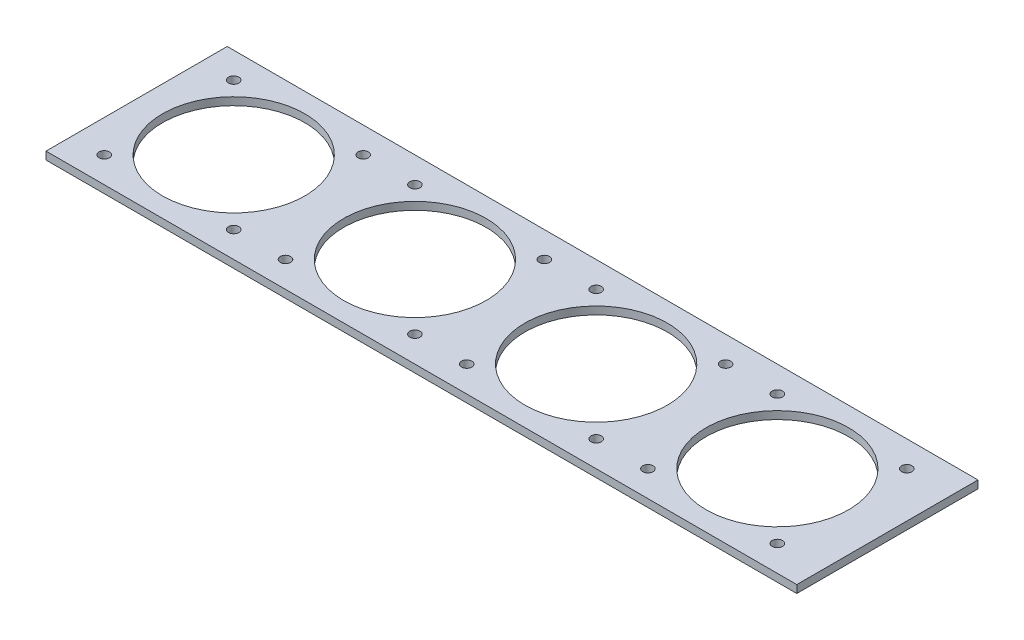
SolidWorks part; units mm, degrees
ref_plane "Ön Düzlem" through (0, 0, 0) normal (0, 0, 1) x (1, 0, 0)
ref_plane "Üst Düzlem" through (0, 0, 0) normal (0, 1, 0) x (1, 0, 0)
ref_plane "Sağ Düzlem" through (0, 0, 0) normal (1, 0, 0) x (0, 0, -1)
sketch "Çizim1" plane through (0, 0, 0) normal (0, 1, 0) x (1, 0, 0)
  line L0 (0, 35) -> (290, 35) construction
  line L1 (0, 0) -> (290, 0)
  line L2 (0, 0) -> (0, 70)
  line L3 (0, 70) -> (290, 70)
  line L4 (290, 0) -> (290, 70)
  line L5 (37.5, 35) -> (37.5, 7.5) construction
  circle A0 centre (37.5, 35) radius 27.5
  circle A1 centre (12.5, 60) radius 2
  circle A2 centre (62.5, 60) radius 2
  circle A3 centre (62.5, 10) radius 2
  circle A4 centre (12.5, 10) radius 2
  circle A5 centre (107.5, 35) radius 27.5
  circle A6 centre (132.5, 60) radius 2
  circle A7 centre (132.5, 10) radius 2
  circle A8 centre (82.5, 10) radius 2
  circle A9 centre (82.5, 60) radius 2
  circle A10 centre (177.5, 35) radius 27.5
  circle A11 centre (202.5, 60) radius 2
  circle A12 centre (202.5, 10) radius 2
  circle A13 centre (152.5, 10) radius 2
  circle A14 centre (152.5, 60) radius 2
  circle A15 centre (247.5, 35) radius 27.5
  circle A16 centre (272.5, 60) radius 2
  circle A17 centre (272.5, 10) radius 2
  circle A18 centre (222.5, 10) radius 2
  circle A19 centre (222.5, 60) radius 2
  point P17 (0, 0)
  dimension "D2" = 55
  dimension "D5" = 4
  dimension "D1" = 70
  dimension "D3" = 37.5
  dimension "D4" = 50
  dimension "D6" = 50
  dimension "D7" = 290
  dimension "D9" = 70
  dimension "D8" = 4
extrude "Yükseklik-Ekstrüzyon1" add sketch "Çizim1" along normal blind 3
